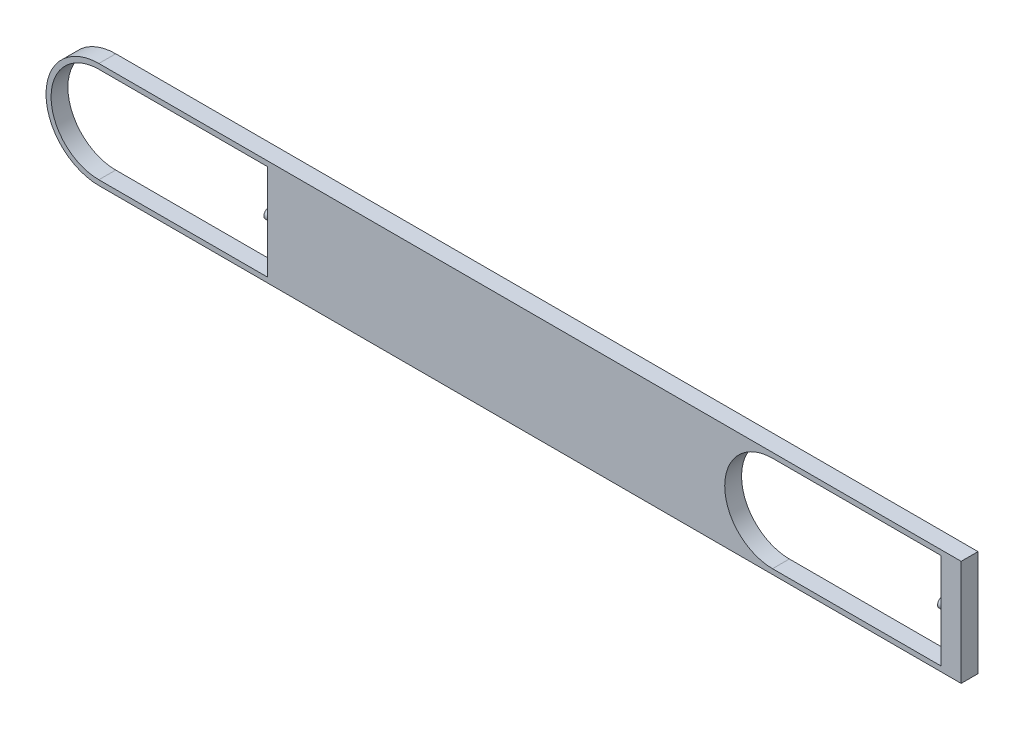
SolidWorks part; units mm, degrees
other "second"
other "first" parameters "D1"=6.35
ref_plane "Front Plane" through (0, 0, 0) normal (0, 0, 1) x (1, 0, 0)
ref_plane "Top Plane" through (0, 0, 0) normal (0, 1, 0) x (1, 0, 0)
ref_plane "Right Plane" through (0, 0, 0) normal (1, 0, 0) x (0, 0, -1)
sketch "Sketch1" plane through (0, 0, 0) normal (0, 0, 1) x (1, 0, 0)
  circle A0 centre (0, 0) radius 19.939
  dimension "D1" = 39.878
extrude "circle extrude" add sketch "Sketch1" along normal blind 6.35
sketch "Sketch3" plane through (0, 0, 0) normal (1, 0, 0) x (0, 0, -1)
  line L0 (0, 21.9329) -> (0, -21.9329) construction
  line L1 (-6.35, 19.939) -> (0, 19.939)
  line L2 (-6.35, 19.939) -> (-6.35, -19.939)
  line L3 (-6.35, -19.939) -> (0, -19.939)
  line L4 (0, 19.939) -> (0, -19.939)
  line L5 (-6.35, -19.939) -> (0, -19.939) construction
extrude "rectangle extrude" add sketch "Sketch3" along normal blind 127
sketch "Sketch2" plane through (0, 0, 6.35) normal (0, 0, 1) x (1, 0, 0)
  circle A0 centre (0, 0) radius 18.034
  dimension "D1" = 36.068
extrude "circle cut" cut sketch "Sketch2" against normal through all
sketch "Sketch6" plane through (0, 0, 6.35) normal (0, 0, 1) x (1, 0, 0)
  line L1 (125.095, -18.034) -> (125.095, 18.034)
  line L3 (0, -18.034) -> (0, 18.034)
  line L4 (0, -18.034) -> (125.095, -18.034)
  line L5 (127, -19.939) -> (0, -19.939) construction
  line L6 (0, 18.034) -> (125.095, 18.034)
  line L8 (127, 19.939) -> (127, -19.939) construction
  arc A0 (0, 19.939) -> (0, -19.939) centre (0, 0) ccw construction
  circle A1 centre (0, 0) radius 18.034 construction
  point P5 (125.095, 0)
  point P12 (0, 0)
  point P17 (-19.939, 0)
  dimension "D1" = 1.905
  dimension "D2" = 1.905
  dimension "D3" = 19.939
extrude "rectangle cut" cut sketch "Sketch6" against normal through all
sketch "Sketch7" plane through (0, 0, 6.35) normal (0, 0, 1) x (1, 0, 0)
  line L1 (63.5, 18.034) -> (125.095, 18.034)
  line L2 (125.095, -18.034) -> (125.095, 18.034) construction
  line L3 (125.095, 18.034) -> (125.095, -18.034)
  line L4 (125.095, -18.034) -> (63.5, -18.034)
  line L5 (63.5, 18.034) -> (63.5, -18.034)
  line L6 (125.095, 18.034) -> (0, 18.034) construction
  dimension "D2" = 63.5
extrude "end shape" add sketch "Sketch7" against normal blind 6.35
sketch "Sketch8" plane through (63.5, 0, 0) normal (-1, 0, 0) x (0, 0, 1)
  line L1 (0, 19.939) -> (6.35, 19.939) construction
  line L2 (3.175, 19.939) -> (3.175, 0) construction
  circle A0 centre (3.175, 0) radius 1.905
  point P2 (0, 0)
  point P8 (0, 0)
  point P9 (0, 0)
  dimension "D1" = 3.81
extrude "for spring extrude" add sketch "Sketch8" along normal blind 2.54
pattern_linear "mirrored pattern" count 2 spacing 254 along (1, 0, 0) of bodies 109
sketch "Sketch10" plane through (127, 0, 0) normal (1, 0, 0) x (0, 0, -1)
  line L1 (-6.35, 19.939) -> (0, 19.939)
  line L2 (-6.35, 19.939) -> (-6.35, -19.939)
  line L3 (-6.35, -19.939) -> (0, -19.939)
  line L4 (0, 19.939) -> (0, -19.939)
extrude "middle connector" add sketch "Sketch10" along normal up to next
sketch "Sketch11" plane through (381, 0, 0) normal (1, 0, 0) x (0, 0, -1)
  line L1 (-6.35, 19.939) -> (0, 19.939)
  line L2 (-6.35, 19.939) -> (-6.35, -19.939)
  line L3 (-6.35, -19.939) -> (0, -19.939)
  line L4 (0, 19.939) -> (0, -19.939)
extrude "end cut" cut sketch "Sketch11" against normal blind 55.88
equation "\"wall_thickness\"= 0.125in"
equation "\"base_thickness\"= 0.25in"
equation "\"D1@circle extrude\"=\"wall_thickness\""
